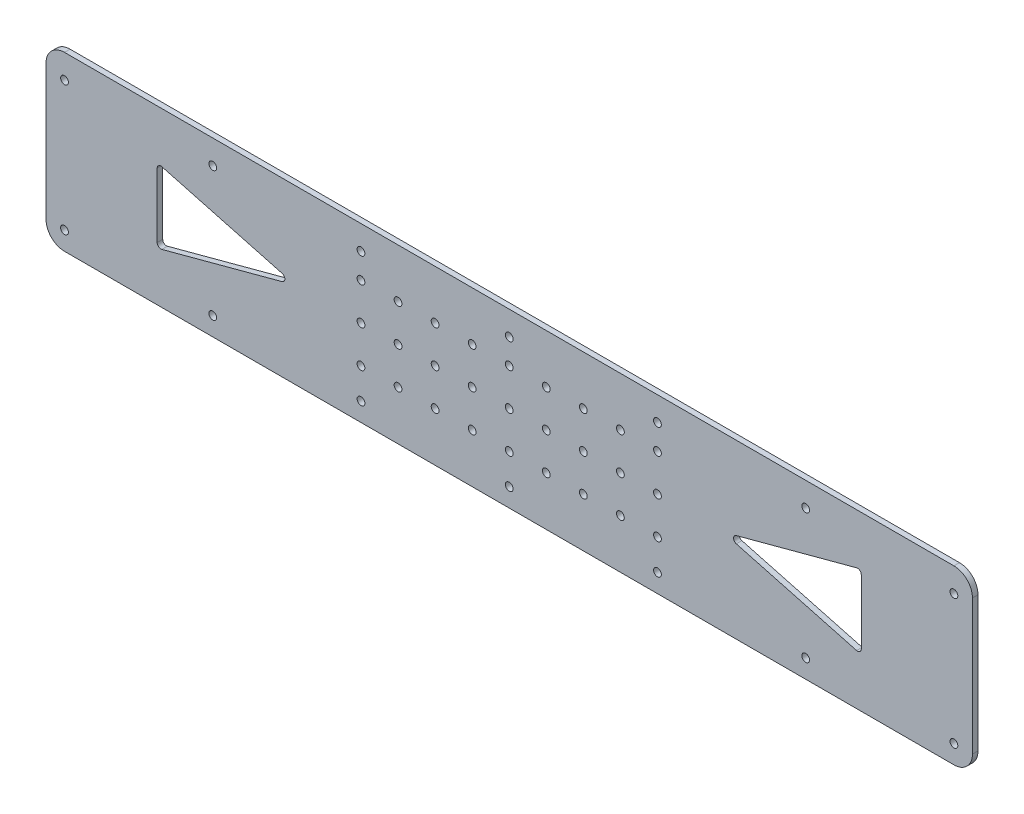
SolidWorks part; units mm, degrees
material "Thornel Mat VMA"
ref_plane "Front Plane" through (0, 0, 0) normal (0, 0, 1) x (1, 0, 0)
ref_plane "Top Plane" through (0, 0, 0) normal (0, 1, 0) x (1, 0, 0)
ref_plane "Right Plane" through (0, 0, 0) normal (1, 0, 0) x (0, 0, -1)
sketch "Sketch1" plane through (0, 0, 0) normal (0, 0, 1) x (1, 0, 0)
  line L1 (-250, -46.5) -> (250, -46.5)
  line L2 (-250, -46.5) -> (-250, 46.5)
  line L3 (-250, 46.5) -> (250, 46.5)
  line L4 (250, -46.5) -> (250, 46.5)
  line L5 (-250, -46.5) -> (250, 46.5) construction
  line L6 (-250, 46.5) -> (250, -46.5) construction
  point P0 (0, 0)
  dimension "D1" = 93
  dimension "D2" = 500
extrude "Boss-Extrude1" add sketch "Sketch1" along normal blind 3
sketch "Sketch2" plane through (0, 0, 3) normal (0, 0, 1) x (1, 0, 0)
  line L0 (-250, 33.5) -> (250, 33.5) construction
  line L1 (-250, 46.5) -> (-250, -46.5) construction
  line L2 (250, -46.5) -> (250, 46.5) construction
  line L3 (250, 46.5) -> (-250, 46.5) construction
  circle A0 centre (-240, 33.5) radius 2.1
  circle A1 centre (-160, 33.5) radius 2.1
  circle A2 centre (-80, 33.5) radius 2.1
  circle A3 centre (0, 33.5) radius 2.1
  circle A4 centre (80, 33.5) radius 2.1
  circle A5 centre (160, 33.5) radius 2.1
  circle A6 centre (240, 33.5) radius 2.1
  dimension "D2" = 10
  dimension "D3" = 4.2
  dimension "D5" = 80
  dimension "D1" = 13
  dimension "D4" = 7
extrude "Cut-Extrude1" cut sketch "Sketch2" against normal through all
pattern_linear "LPattern1" count 2 spacing 70 along (0, -1, 0) of "Cut-Extrude1"
fillet "Fillet1" radius 10 4 edges at (250, -46.5, 1.5) (-250, -46.5, 1.5) (250, 46.5, 1.5) (-250, 46.5, 1.5)
sketch "Sketch3" plane through (0, 0, 3) normal (0, 0, 1) x (1, 0, 0)
  line L0 (0, 0) -> (-250, 0) construction
  line L1 (-250, 36.5) -> (-250, -36.5) construction
  line L2 (-190, -17.3935) -> (-190, 17.3935)
  line L3 (-187.4824, 19.3254) -> (-122.5688, 1.9319)
  line L4 (-187.4824, -19.3254) -> (-122.5688, -1.9319)
  line L5 (0, 0) -> (0, 46.5) construction
  line L6 (240, 46.5) -> (-240, 46.5) construction
  line L7 (190, -17.3935) -> (190, 17.3935)
  line L8 (187.4824, 19.3254) -> (122.5688, 1.9319)
  line L9 (187.4824, -19.3254) -> (122.5688, -1.9319)
  arc A0 (-122.5688, -1.9319) -> (-122.5688, 1.9319) centre (-123.0864, 0) ccw
  arc A1 (-190, 17.3935) -> (-187.4824, 19.3254) centre (-188, 17.3935) cw
  arc A2 (-187.4824, -19.3254) -> (-190, -17.3935) centre (-188, -17.3935) cw
  arc A3 (187.4824, -19.3254) -> (190, -17.3935) centre (188, -17.3935) ccw
  arc A4 (190, 17.3935) -> (187.4824, 19.3254) centre (188, 17.3935) ccw
  arc A5 (122.5688, -1.9319) -> (122.5688, 1.9319) centre (123.0864, 0) cw
  point P9 (-190, 0)
  point P12 (-115.359, 0)
  point P15 (-190, 20)
  point P18 (-190, -20)
  dimension "D4" = 2
  dimension "D1" = 15
  dimension "D2" = 20
  dimension "D3" = 60
extrude "Cut-Extrude2" cut sketch "Sketch3" against normal through all
sketch "Sketch4" plane through (0, 0, 3) normal (0, 0, 1) x (1, 0, 0)
  line L0 (0, 0) -> (-80, 0) construction
  line L1 (0, 0) -> (0, -46.5) construction
  line L2 (-240, -46.5) -> (240, -46.5) construction
  circle A0 centre (-80, 0) radius 2.1
  circle A1 centre (-60, 0) radius 2.1
  circle A2 centre (-40, 0) radius 2.1
  circle A3 centre (-20, 0) radius 2.1
  circle A4 centre (0, 0) radius 2.1
  circle A5 centre (20, 0) radius 2.1
  circle A6 centre (40, 0) radius 2.1
  circle A7 centre (60, 0) radius 2.1
  circle A8 centre (80, 0) radius 2.1
  circle A9 centre (-80, -20) radius 2.1
  circle A10 centre (-60, -20) radius 2.1
  circle A11 centre (-40, -20) radius 2.1
  circle A12 centre (-20, -20) radius 2.1
  circle A13 centre (0, -20) radius 2.1
  circle A14 centre (20, -20) radius 2.1
  circle A15 centre (40, -20) radius 2.1
  circle A16 centre (60, -20) radius 2.1
  circle A17 centre (80, -20) radius 2.1
  circle A18 centre (80, 20) radius 2.1
  circle A19 centre (60, 20) radius 2.1
  circle A20 centre (40, 20) radius 2.1
  circle A21 centre (20, 20) radius 2.1
  circle A22 centre (0, 20) radius 2.1
  circle A23 centre (-20, 20) radius 2.1
  circle A24 centre (-40, 20) radius 2.1
  circle A25 centre (-60, 20) radius 2.1
  circle A26 centre (-80, 20) radius 2.1
  dimension "D2" = 4.2
  dimension "D4" = 20
  dimension "D1" = 80
  dimension "D5" = 2
  dimension "D6" = 20
  dimension "D3" = 5
extrude "Cut-Extrude3" cut sketch "Sketch4" against normal through all
